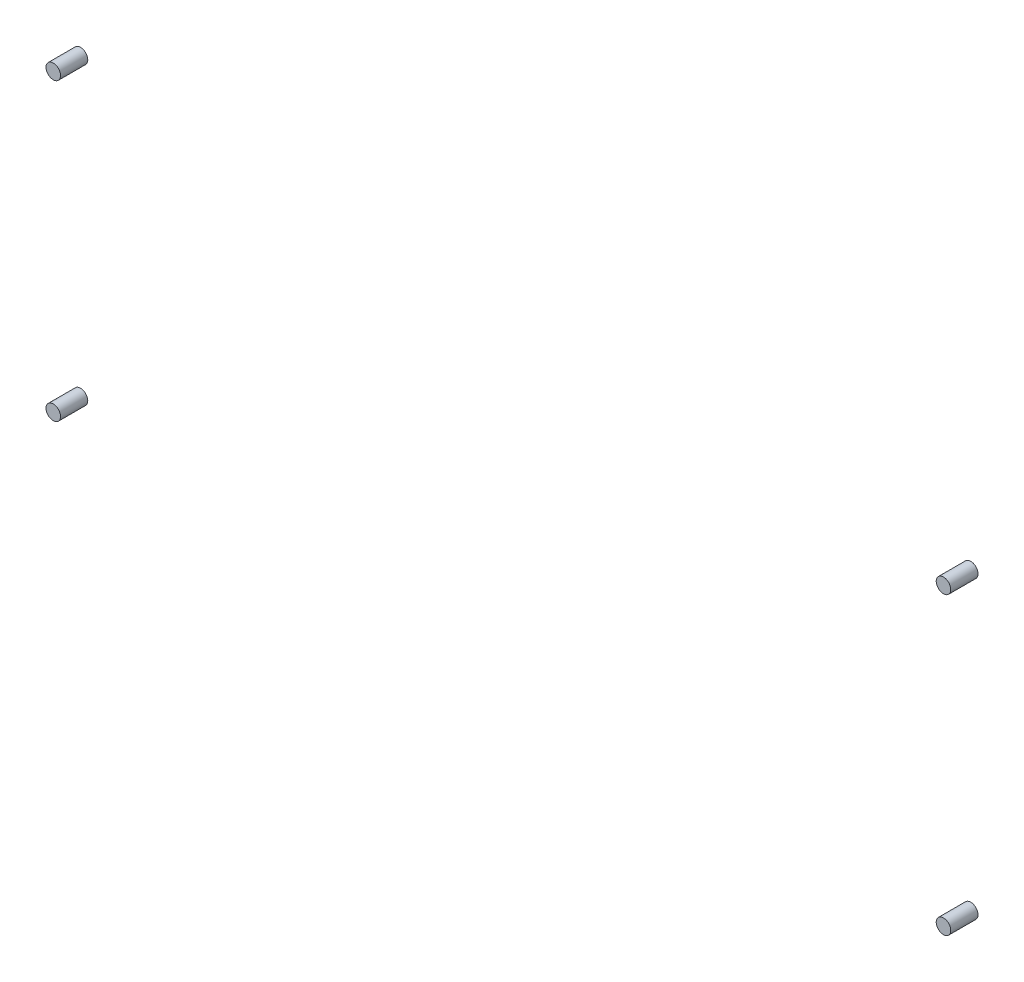
SolidWorks part; units mm, degrees
ref_plane "前视基准面" through (0, 0, 0) normal (0, 0, 1) x (1, 0, 0)
ref_plane "上视基准面" through (0, 0, 0) normal (0, 1, 0) x (1, 0, 0)
ref_plane "右视基准面" through (0, 0, 0) normal (1, 0, 0) x (0, 0, -1)
other "Configuration Table"
sketch "草图1" plane through (0, 0, 0) normal (0, 0, 1) x (1, 0, 0)
  line L0 (0, -95) -> (432, -95)
  line L1 (432, -95) -> (432, 235)
  line L2 (432, 235) -> (0, 235)
  line L3 (0, 235) -> (0, -95)
extrude "凸台-拉伸1" add sketch "草图1" along normal blind 12
sketch "草图2" plane through (0, 0, 12) normal (0, 0, 1) x (1, 0, 0)
  circle A0 centre (20, -42) radius 3.2
  circle A1 centre (412, -42) radius 3.2
  circle A2 centre (20, 88) radius 3.2
  circle A3 centre (412, 88) radius 3.2
extrude "切除-拉伸1" cut sketch "草图2" against normal through all flip side to cut
